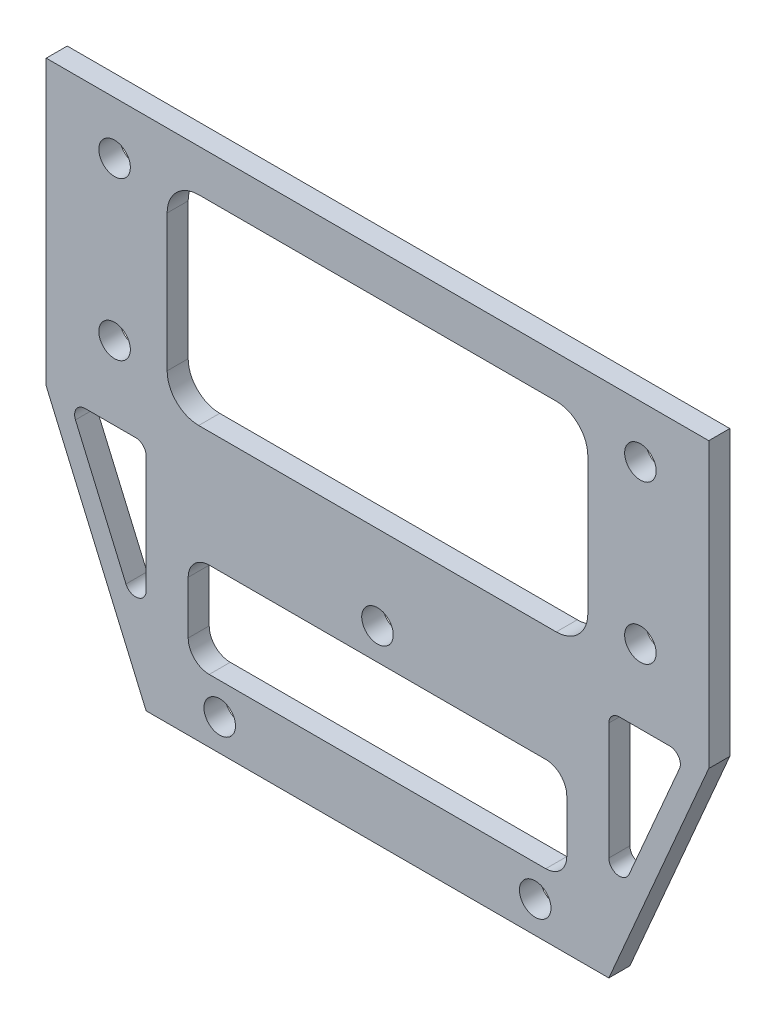
SolidWorks part; units mm, degrees
material "Thornel Mat VMA"
ref_plane "前视基准面" through (0, 0, 0) normal (0, 0, 1) x (1, 0, 0)
ref_plane "上视基准面" through (0, 0, 0) normal (0, 1, 0) x (1, 0, 0)
ref_plane "右视基准面" through (0, 0, 0) normal (1, 0, 0) x (0, 0, -1)
sketch "草图1" plane through (0, 0, 0) normal (0, 0, 1) x (1, 0, 0)
  line L0 (0, 56.3346) -> (0, -62.4729) construction
  line L1 (-61.7675, 0) -> (113.1776, 0) construction
  line L2 (-31.5, -2) -> (-22, -2)
  line L7 (-31.5, 25) -> (31.5, 25)
  line L8 (-31.5, 25) -> (-31.5, -24) construction
  line L9 (-31.5, -24) -> (31.5, -24) construction
  line L10 (31.5, 25) -> (31.5, -24) construction
  line L11 (-20, 21) -> (20, 21)
  line L12 (-20, 21) -> (-20, 2)
  line L13 (-20, 2) -> (20, 2)
  line L14 (20, 21) -> (20, 2)
  line L15 (-20, 21) -> (20, 2) construction
  line L16 (-20, 2) -> (20, 21) construction
  line L17 (-18, -9) -> (18, -9)
  line L18 (-18, -9) -> (-18, -18)
  line L19 (-18, -18) -> (18, -18)
  line L20 (18, -9) -> (18, -18)
  line L21 (-18, -9) -> (18, -18) construction
  line L22 (-18, -18) -> (18, -9) construction
  line L23 (-22, -2) -> (-22, -24)
  line L24 (31.5, -2) -> (22, -2)
  line L25 (22, -2) -> (22, -24)
  line L26 (-31.5, -2) -> (-31.5, 25)
  line L27 (31.5, -2) -> (31.5, 25)
  line L28 (22, -24) -> (-22, -24)
  circle A0 centre (-25, 20) radius 1.5
  circle A1 centre (25, 20) radius 1.5
  circle A2 centre (-25, 5) radius 1.5
  circle A3 centre (25, 5) radius 1.5
  circle A4 centre (0, -6) radius 1.5
  circle A5 centre (-15, -21) radius 1.5
  circle A6 centre (15, -21) radius 1.5
  point P19 (0, -13.5)
  point P20 (0, 11.5)
  dimension "D1" = 3
  dimension "D2" = 30
  dimension "D3" = 15
  dimension "D4" = 50
  dimension "D5" = 15
  dimension "D6" = 5
  dimension "D7" = 6
  dimension "D8" = 5
  dimension "D10" = 6.5
  dimension "D9" = 3
  dimension "D11" = 4
  dimension "D12" = 5
  dimension "D13" = 2
  dimension "D14" = 3
  dimension "D15" = 3
  dimension "D16" = 5.5
  dimension "D17" = 2
  dimension "D18" = 4
extrude "凸台-拉伸1" add sketch "草图1" along normal blind 2
sketch "草图2" plane through (0, 0, 2) normal (0, 0, 1) x (1, 0, 0)
  line L0 (-31.5, -2) -> (-22, -24)
  line L1 (-22, -24) -> (-22, -18.955)
  line L2 (-22, -2) -> (-22, -24) construction
  line L3 (-22, -18.955) -> (-29.3215, -2)
  line L4 (-31.5, -2) -> (-22, -2) construction
  line L5 (-29.3215, -2) -> (-31.5, -2)
  line L6 (31.5, -2) -> (22, -24)
  line L7 (22, -24) -> (22, -18.955)
  line L8 (22, -24) -> (22, -2) construction
  line L9 (22, -18.955) -> (29.3215, -2)
  line L10 (22, -2) -> (31.5, -2) construction
  line L11 (29.3215, -2) -> (31.5, -2)
  dimension "D1" = 2
extrude "凸台-拉伸2" add sketch "草图2" against normal up to surface (2 mm away) up to face at (-13.5, -21, 0)
fillet "圆角1" radius 3 4 edges at (20, 2, 1) (20, 21, 1) (-20, 21, 1) (-20, 2, 1)
fillet "圆角2" radius 2 4 edges at (-18, -18, 1) (18, -18, 1) (18, -9, 1) (-18, -9, 1)
fillet "圆角3" radius 1 6 edges at (29.3215, -2, 1) (-29.3215, -2, 1) (22, -18.955, 1) (-22, -18.955, 1) (22, -2, 1) (-22, -2, 1)
